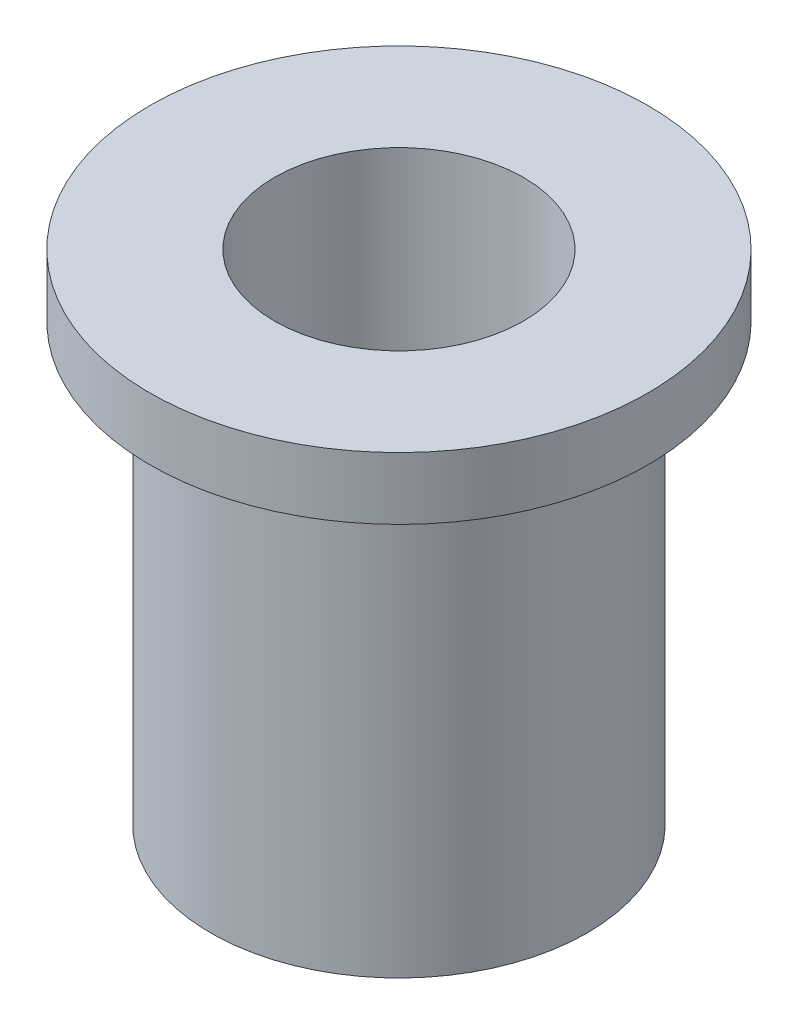
SolidWorks part; units mm, degrees
ref_plane "Front Plane" through (0, 0, 0) normal (0, 0, 1) x (1, 0, 0)
ref_plane "Top Plane" through (0, 0, 0) normal (0, 1, 0) x (1, 0, 0)
ref_plane "Right Plane" through (0, 0, 0) normal (1, 0, 0) x (0, 0, -1)
sketch "Sketch1" plane through (0, 0, 0) normal (0, 0, 1) x (1, 0, 0)
  line L0 (5.4421, 36.3217) -> (5.4421, -37.9895) construction
  line L1 (8.6171, -14.9119) -> (8.6171, -27.6119)
  line L2 (8.6171, -27.6119) -> (10.2427, -27.6119)
  line L3 (10.2427, -27.6119) -> (10.2427, -16.4994)
  line L4 (10.2427, -16.4994) -> (11.7921, -16.4994)
  line L5 (11.7921, -16.4994) -> (11.7921, -14.9119)
  line L6 (11.7921, -14.9119) -> (8.6171, -14.9119)
  dimension "D1" = 6.35
  dimension "D2" = 12.7
  dimension "D3" = 9.6012
  dimension "D4" = 12.7
  dimension "D5" = 1.5875
revolve "Revolve1" add sketch "Sketch1" angle 360 about L0
